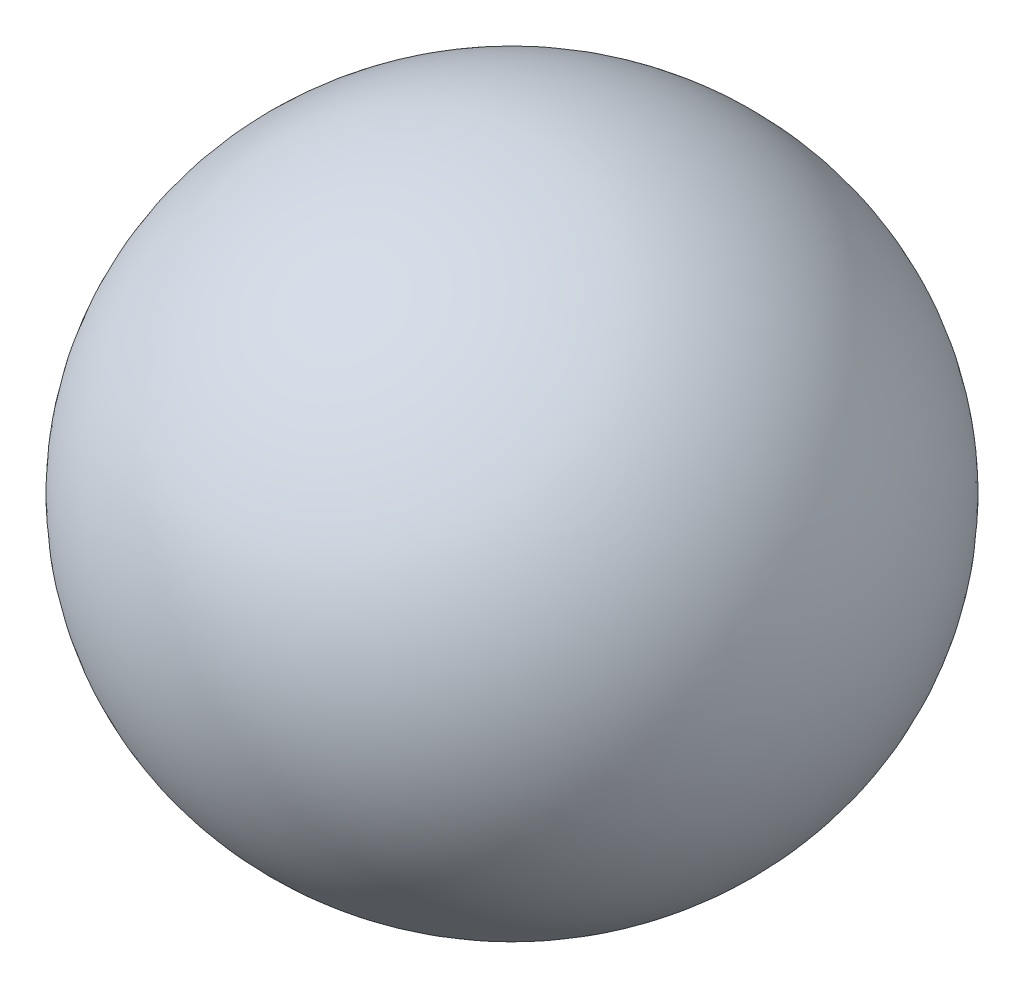
SolidWorks part; units mm, degrees
ref_plane "Front Plane" through (0, 0, 0) normal (0, 0, 1) x (1, 0, 0)
ref_plane "Top Plane" through (0, 0, 0) normal (0, 1, 0) x (1, 0, 0)
ref_plane "Right Plane" through (0, 0, 0) normal (1, 0, 0) x (0, 0, -1)
sketch "Sketch2" plane through (0, 0, 0) normal (0, 0, 1) x (1, 0, 0)
  line L0 (0, 0) -> (0, 40.64)
  line L1 (0, 0) -> (43.18, 0)
  ellipse E0 centre (0, 0) end of major axis (43.18, 0) minor radius 40.64 (0, 40.64) -> (43.18, 0) cw
revolve "Revolve1" add sketch "Sketch2" angle 360 about L0
mirror "Mirror1" about plane through (0, 0, 0) normal (0, -1, 0) of "Revolve1"
